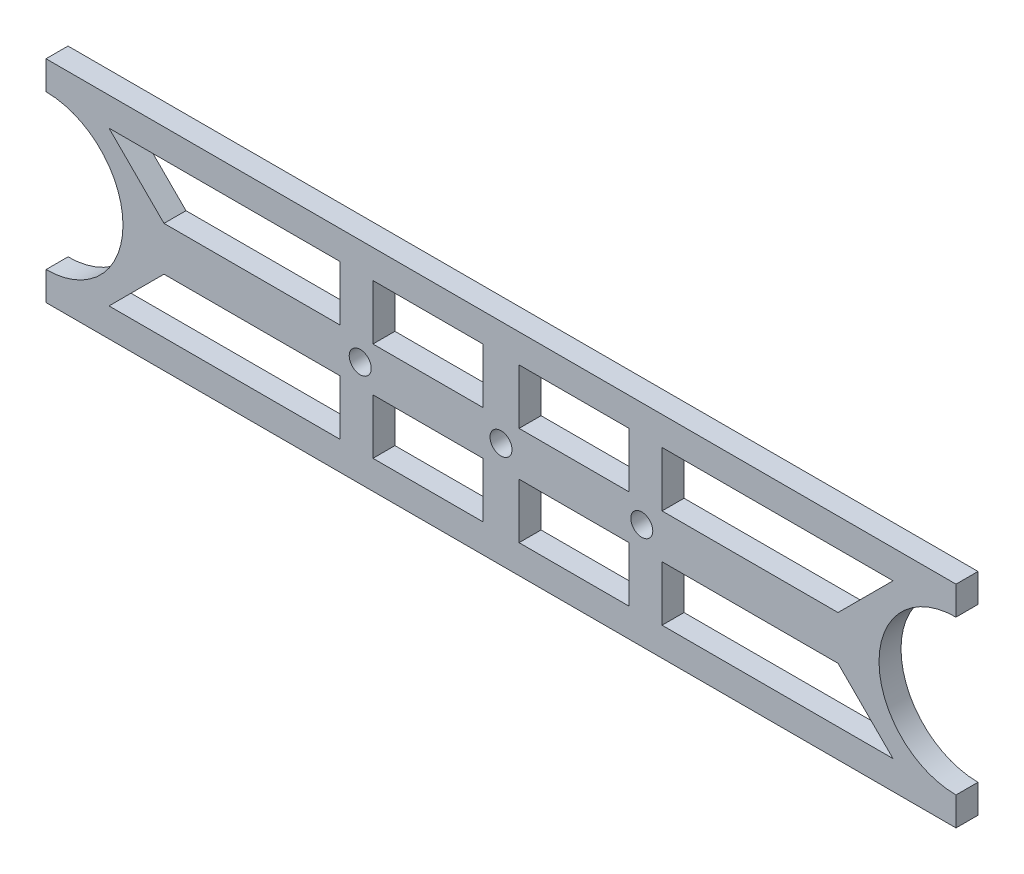
SolidWorks part; units mm, degrees
material "AISI 304"
ref_plane "Front" through (0, 0, 0) normal (0, 0, 1) x (1, 0, 0)
ref_plane "Top" through (0, 0, 0) normal (0, 1, 0) x (1, 0, 0)
ref_plane "Right" through (0, 0, 0) normal (1, 0, 0) x (0, 0, -1)
sketch "Sketch1" plane through (0, 0, 0) normal (0, 0, 1) x (1, 0, 0)
  line L0 (-32, 0) -> (0, 0) construction
  line L1 (-103.428, -24) -> (103.428, -24)
  line L2 (-103.428, -24) -> (-103.428, 24)
  line L3 (-103.428, 24) -> (103.428, 24)
  line L4 (103.428, -24) -> (103.428, 24)
  line L5 (-103.428, -24) -> (103.428, 24) construction
  line L6 (-103.428, 24) -> (103.428, -24) construction
  line L7 (0, 0) -> (32, 0) construction
  circle A0 centre (0, 0) radius 2.5
  circle A1 centre (32, 0) radius 2.5
  circle A2 centre (-32, 0) radius 2.5
  point P0 (0, 0)
  dimension "D1" = 5
  dimension "D2" = 206.856
  dimension "D3" = 48
  dimension "D4" = 32
extrude "Boss-Extrude1" add sketch "Sketch1" along normal blind 5
sketch "Sketch2" plane through (0, 0, 5) normal (0, 0, 1) x (1, 0, 0)
  line L0 (103.428, -24) -> (103.428, 24) construction
  line L1 (89.1082, 17.5) -> (36.6082, 17.5)
  line L2 (89.1082, 17.5) -> (76.6082, 5)
  line L3 (89.1082, 17.5) -> (103.428, 17.5) construction
  line L4 (4.1082, 17.5) -> (29.1082, 17.5)
  line L5 (4.1082, 17.5) -> (4.1082, 5)
  line L6 (4.1082, 5) -> (29.1082, 5)
  line L7 (29.1082, 17.5) -> (29.1082, 5)
  line L16 (36.6082, 17.5) -> (36.6082, 5)
  line L17 (36.6082, 5) -> (76.6082, 5)
  line L18 (2.75, 0) -> (-2.75, 0) construction
  line L19 (89.1082, -17.5) -> (36.6082, -17.5)
  line L20 (36.6082, -17.5) -> (36.6082, -5)
  line L21 (36.6082, -5) -> (76.6082, -5)
  line L22 (89.1082, -17.5) -> (76.6082, -5)
  line L23 (4.1082, -5) -> (29.1082, -5)
  line L24 (29.1082, -17.5) -> (29.1082, -5)
  line L25 (4.1082, -17.5) -> (29.1082, -17.5)
  line L26 (4.1082, -17.5) -> (4.1082, -5)
  circle A0 centre (103.428, 0) radius 17.5
  dimension "D1" = 35
  dimension "D2" = 12.5
  dimension "D3" = 25
  dimension "D4" = 52.5
  dimension "D5" = 22.5
  dimension "D6" = 45
  dimension "D7" = 7.5
extrude "Cut-Extrude1" cut sketch "Sketch2" against normal through all
mirror "Mirror1" about plane through (0, 0, 0) normal (1, 0, 0) of "Cut-Extrude1"
